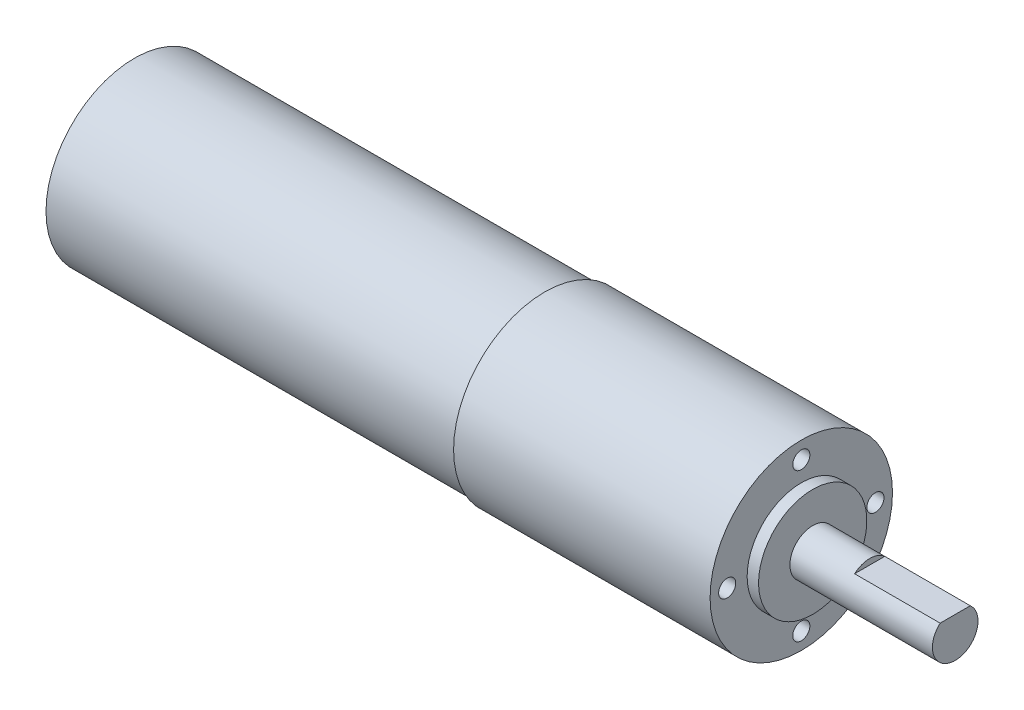
SolidWorks part; units mm, degrees
ref_plane "Front Plane" through (0, 0, 0) normal (0, 0, 1) x (1, 0, 0)
ref_plane "Top Plane" through (0, 0, 0) normal (0, 1, 0) x (1, 0, 0)
ref_plane "Right Plane" through (0, 0, 0) normal (1, 0, 0) x (0, 0, -1)
sketch "Sketch1" plane through (0, 0, 0) normal (0, 0, 1) x (1, 0, 0)
  line L0 (0, 0) -> (0, 15.5)
  line L1 (0, 15.5) -> (72, 15.5)
  line L2 (72, 15.5) -> (72, 16)
  line L3 (72, 16) -> (117, 16)
  line L4 (117, 16) -> (117, 9.5)
  line L5 (117, 9.5) -> (119, 9.5)
  line L6 (119, 9.5) -> (119, 4)
  line L7 (119, 4) -> (144, 4)
  line L8 (144, 4) -> (144, 0)
  line L9 (0, 0) -> (144, 0) construction
  line L10 (0, 0) -> (144, 0)
  dimension "D1" = 31
  dimension "D2" = 32
  dimension "D3" = 72
  dimension "D4" = 45
  dimension "D5" = 19
  dimension "D6" = 8
  dimension "D7" = 2
  dimension "D8" = 25
revolve "Revolve1" add sketch "Sketch1" angle 360 about L9
sketch "Sketch2" plane through (144, 0, 0) normal (1, 0, 0) x (0, 0, -1)
  line L0 (-2.6458, 3) -> (2.6458, 3)
  arc A0 (2.6458, 3) -> (-2.6458, 3) centre (0, 0) ccw
  circle A1 centre (0, 0) radius 4 construction
  dimension "D1" = 3
extrude "Cut-Extrude1" cut sketch "Sketch2" against normal blind 15
sketch "Sketch3" plane through (117, 0, 0) normal (1, 0, 0) x (0, 0, -1)
  circle A0 centre (0, 0) radius 13 construction
  circle A1 centre (0, 13) radius 1.5
  circle A3 centre (13, 0) radius 1.5
  circle A4 centre (0, -13) radius 1.5
  circle A5 centre (-13, 0) radius 1.5
  point P14 (0, 0)
  dimension "D1" = 26
  dimension "D2" = 3
  dimension "D3" = 4
extrude "Cut-Extrude2" cut sketch "Sketch3" against normal blind 5
